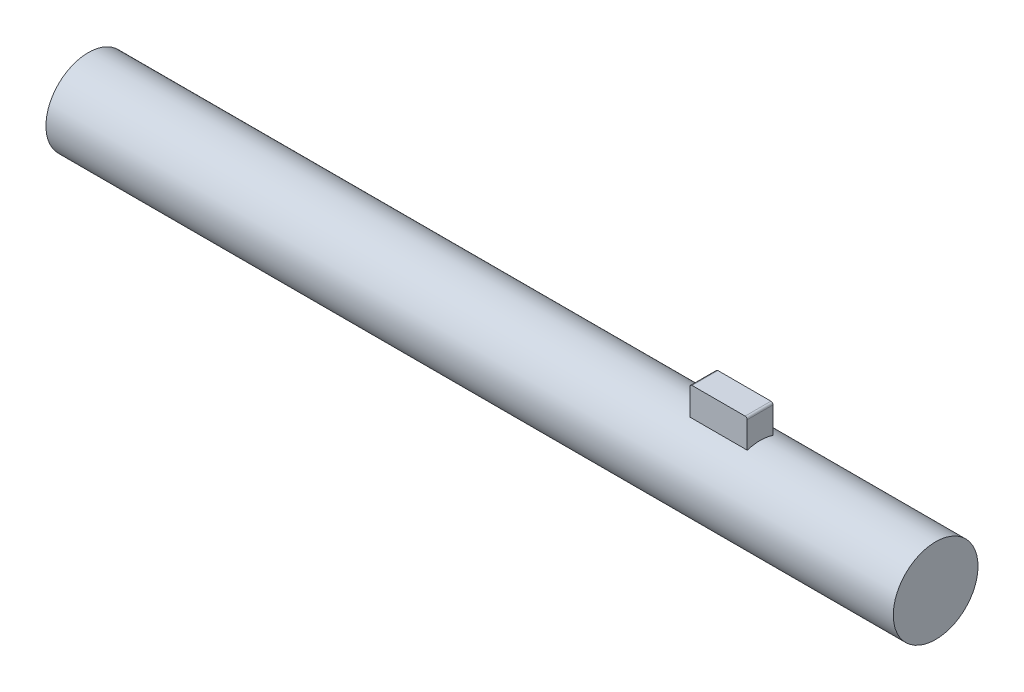
SolidWorks part; units mm, degrees
ref_plane "Front Plane" through (0, 0, 0) normal (0, 0, 1) x (1, 0, 0)
ref_plane "Top Plane" through (0, 0, 0) normal (0, 1, 0) x (1, 0, 0)
ref_plane "Right Plane" through (0, 0, 0) normal (1, 0, 0) x (0, 0, -1)
sketch "Sketch1" plane through (0, 0, 0) normal (1, 0, 0) x (0, 0, -1)
  circle A0 centre (0, 0) radius 4
  dimension "D1" = 8
extrude "Boss-Extrude1" add sketch "Sketch1" along normal blind 80
ref_plane "Plane1" through (0, 4, 0) normal (0, 1, 0) x (1, 0, 0)
sketch "Sketch2" plane through (0, 4, 0) normal (0, 1, 0) x (1, 0, 0)
  line L1 (58.0268, -1.2193) -> (63.4325, -1.2193)
  line L2 (58.0268, -1.2193) -> (58.0268, 1.2193)
  line L3 (58.0268, 1.2193) -> (63.4325, 1.2193)
  line L4 (63.4325, -1.2193) -> (63.4325, 1.2193)
  line L5 (58.0268, -1.2193) -> (63.4325, 1.2193) construction
  line L6 (58.0268, 1.2193) -> (63.4325, -1.2193) construction
  point P0 (60.7296, 0)
extrude "Boss-Extrude3" add sketch "Sketch2" along normal blind 2.5 and the other way up to surface other way up to face at (80, 0, -4)
fillet "Fillet2" radius 0.2 2 edges at (58.0268, 6.5, 0) (63.4325, 6.5, 0)
